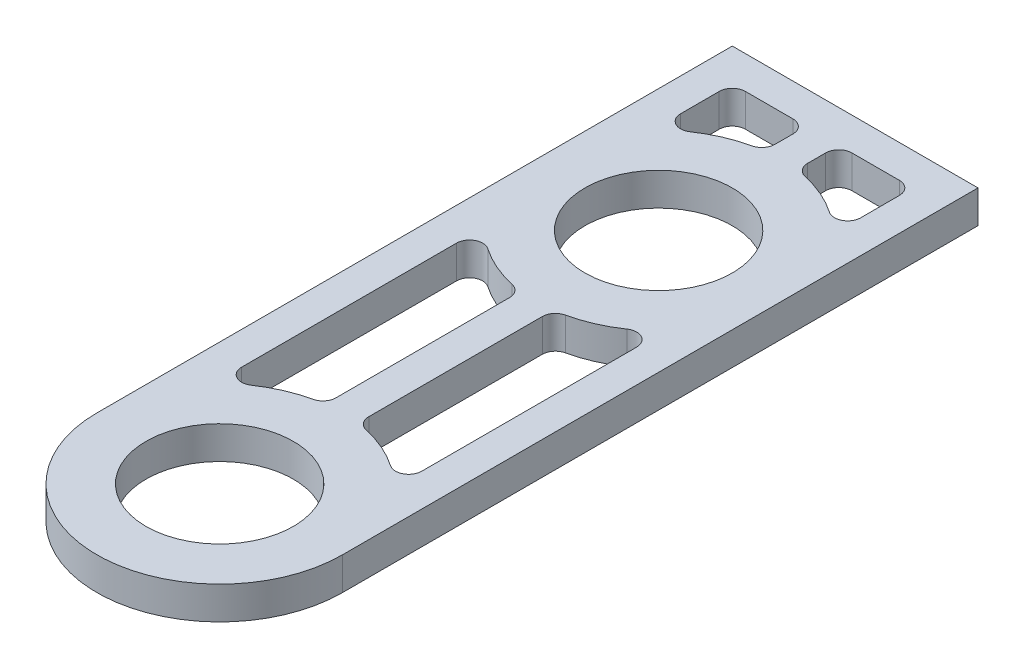
SolidWorks part; units mm, degrees
ref_plane "Front Plane" through (0, 0, 0) normal (0, 0, 1) x (1, 0, 0)
ref_plane "Top Plane" through (0, 0, 0) normal (0, 1, 0) x (1, 0, 0)
ref_plane "Right Plane" through (0, 0, 0) normal (1, 0, 0) x (0, 0, -1)
sketch "Sketch1" plane through (0, 0, 0) normal (0, 1, 0) x (1, 0, 0)
  line L0 (-23.8125, 69.85) -> (23.8125, 69.85) construction
  line L1 (-23.8125, -76.2) -> (23.8125, -76.2)
  line L2 (-23.8125, -76.2) -> (-23.8125, 76.2)
  line L3 (-23.8125, 76.2) -> (23.8125, 76.2)
  line L4 (23.8125, -76.2) -> (23.8125, 76.2)
  line L5 (-23.8125, -76.2) -> (23.8125, 76.2) construction
  line L6 (-23.8125, 76.2) -> (23.8125, -76.2) construction
  line L8 (7.3323, -46.99) -> (3.6662, -40.64)
  line L9 (3.6662, -40.64) -> (-3.6662, -40.64)
  line L10 (-3.6662, -40.64) -> (-7.3323, -46.99)
  line L11 (-7.3323, -46.99) -> (-3.6662, -53.34)
  line L12 (-3.6662, -53.34) -> (3.6662, -53.34)
  line L13 (3.6662, -53.34) -> (7.3323, -46.99)
  line L14 (5.4993, 38.1) -> (2.7496, 42.8625)
  line L15 (2.7496, 42.8625) -> (-2.7496, 42.8625)
  line L16 (-2.7496, 42.8625) -> (-5.4993, 38.1)
  line L17 (-5.4993, 38.1) -> (-2.7496, 33.3375)
  line L18 (-2.7496, 33.3375) -> (2.7496, 33.3375)
  line L19 (2.7496, 33.3375) -> (5.4993, 38.1)
  circle A0 centre (0, 38.1) radius 14.2875
  circle A1 centre (0, 38.1) radius 4.7625 construction
  circle A2 centre (0, -46.99) radius 14.2875
  circle A3 centre (0, -46.99) radius 6.35 construction
  circle A4 centre (0, 38.1) radius 31.75
  circle A5 centre (0, -46.99) radius 53.34
  point P0 (0, 0)
  dimension "D3" = 28.575
  dimension "D4" = 9.525
  dimension "D5" = 28.575
  dimension "D7" = 12.7
  dimension "D9" = 63.5
  dimension "D10" = 106.68
  dimension "D1" = 47.625
  dimension "D2" = 6.35
  dimension "D6" = 85.09
  dimension "D8" = 152.4
  dimension "D11" = 31.75
extrude "Boss-Extrude1" add sketch "Sketch1" along normal blind 6.35 contours A4 A0 | L4 A5 L2 L1 A2 | A5 L4 L3 L2 A4 | A5 L4 A4 | A5 A4 L2
sketch "Sketch2" plane through (0, 6.35, 0) normal (0, 1, 0) x (1, 0, 0)
  line L0 (-23.8125, 76.2) -> (23.8125, 76.2)
  line L1 (23.8125, 76.2) -> (23.8125, 38.1)
  line L2 (23.8125, -76.2) -> (23.8125, 76.2) construction
  line L3 (23.8125, 38.1) -> (23.8125, -46.99)
  line L4 (-23.8125, 76.2) -> (-23.8125, 38.1)
  line L5 (-23.8125, -76.2) -> (-23.8125, 76.2) construction
  line L6 (-23.8125, 38.1) -> (-23.8125, -46.99)
  line L7 (-17.4625, 21.9106) -> (-17.4625, -30.8006)
  line L8 (17.4625, 21.9106) -> (17.4625, -30.8006)
  line L9 (-17.4625, 54.2894) -> (-17.4625, 69.85)
  line L10 (-17.4625, 69.85) -> (17.4625, 69.85)
  line L11 (0, 38.1) -> (0, -46.99) construction
  line L12 (3.175, 14.5001) -> (3.175, -23.3901)
  line L13 (-3.175, 14.5001) -> (-3.175, -23.3901)
  line L14 (17.4625, 69.85) -> (17.4625, 54.2894)
  line L15 (0, 38.1) -> (0, 69.85) construction
  line L16 (-3.175, 61.6999) -> (-3.175, 69.85)
  line L17 (3.175, 61.6999) -> (3.175, 69.85)
  circle A0 centre (0, 38.1) radius 23.8125
  circle A1 centre (0, -46.99) radius 23.8125
  dimension "D1" = 47.625
  dimension "D2" = 47.625
  dimension "D3" = 6.35
  dimension "D4" = 6.35
  dimension "D5" = 6.35
  dimension "D6" = 6.35
  dimension "D7" = 6.35
  dimension "D8" = 6.35
extrude "Cut-Extrude1" cut sketch "Sketch2" against normal through all
fillet "Fillet1" radius 2.54 16 edges at (-17.4625, 3.175, 30.8006) (-3.175, 3.175, 23.3901) (17.4625, 3.175, 30.8006) (3.175, 3.175, 23.3901) (-3.175, 3.175, -14.5001) (3.175, 3.175, -14.5001) (-17.4625, 3.175, -21.9106) (17.4625, 3.175, -21.9106) (17.4625, 3.175, -54.2894) (3.175, 3.175, -61.6999) (17.4625, 3.175, -69.85) (3.175, 3.175, -69.85) (-3.175, 3.175, -61.6999) (-17.4625, 3.175, -54.2894) (-3.175, 3.175, -69.85) (-17.4625, 3.175, -69.85)
